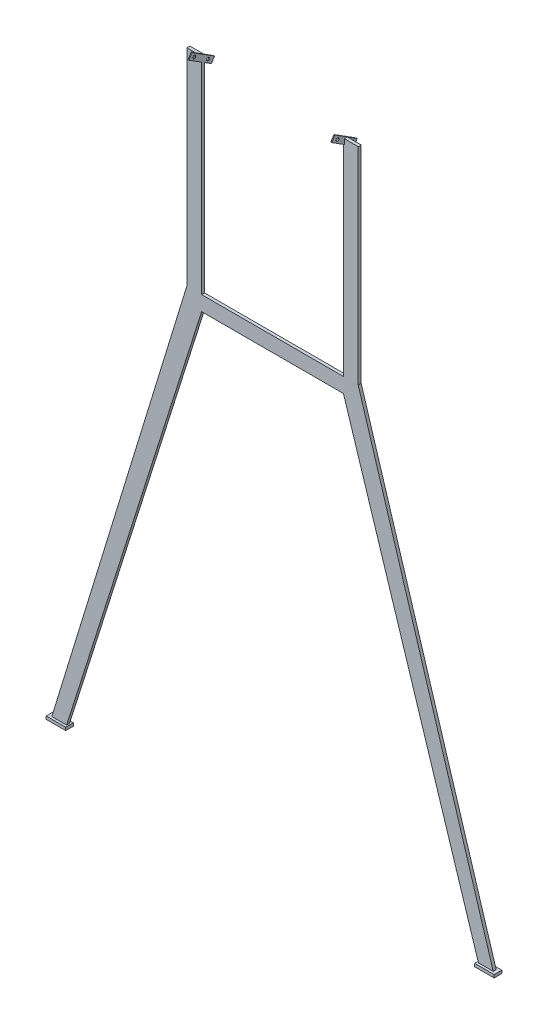
SolidWorks part; units mm, degrees
ref_plane "Front Plane" through (0, 0, 0) normal (0, 0, 1) x (1, 0, 0)
ref_plane "Top Plane" through (0, 0, 0) normal (0, 1, 0) x (1, 0, 0)
ref_plane "Right Plane" through (0, 0, 0) normal (1, 0, 0) x (0, 0, -1)
sketch "Sketch2" plane through (0, 0, 0) normal (0, 0, 1) x (1, 0, 0)
  line L1 (-670.4947, 662.5442) -> (829.5053, 662.5442)
  line L2 (-670.4947, 662.5442) -> (-670.4947, -1536.0258)
  line L3 (-670.4947, -1536.0258) -> (829.5053, -1536.0258)
  line L4 (829.5053, 662.5442) -> (829.5053, -1536.0258)
  line L5 (-160.4947, 662.5442) -> (319.5053, 662.5442)
  dimension "D1" = 1500
  dimension "D2" = 2198.57
extrude "Boss-Extrude1" add sketch "Sketch2" along normal blind 10 contours L4 L1 L2 L3
sketch "Sketch3" plane through (0, 0, 10) normal (0, 0, 1) x (1, 0, 0)
  line L0 (-670.4947, 662.5442) -> (829.5053, 662.5442) construction
  line L1 (-160.4947, 662.5442) -> (319.5053, 662.5442)
  line L2 (-160.4947, 662.5442) -> (-160.4947, -36.0262)
  line L3 (-160.4947, -36.0262) -> (319.5053, -36.0262)
  line L4 (319.5053, 662.5442) -> (319.5053, -36.0262)
  line L5 (-210.4947, 662.5442) -> (-210.4947, -36.0262)
  line L6 (-210.4947, -36.0262) -> (-670.4947, -36.0262)
  line L7 (-670.4947, 662.5442) -> (-670.4947, -1536.0258) construction
  line L8 (-670.4947, -36.0262) -> (-670.4947, 662.5442)
  line L9 (-670.4947, 662.5442) -> (-210.4947, 662.5442)
  line L10 (369.5053, 662.5442) -> (369.5053, -36.0262)
  line L11 (369.5053, -36.0262) -> (829.5053, -36.0262)
  line L12 (829.5053, 662.5442) -> (829.5053, -1536.0258) construction
  line L13 (829.5053, -36.0262) -> (829.5053, 662.5442)
  line L14 (829.5053, 662.5442) -> (369.5053, 662.5442)
  dimension "D1" = 510
  dimension "D2" = 480
  dimension "D3" = 698.5704
  dimension "D4" = 460
  dimension "D5" = 460
extrude "Cut-Extrude1" cut sketch "Sketch3" against normal through all
sketch "Sketch9" plane through (0, 0, 0) normal (0, 0, -1) x (-1, 0, 0)
  line L0 (-369.5053, -36.0262) -> (-829.5053, -36.0262)
  line L5 (-369.5053, -36.0262) -> (-829.5053, -1536.0258)
  line L6 (-829.5053, -36.0262) -> (-829.5053, -1536.0258)
  line L7 (210.4947, -36.0262) -> (670.4947, -1536.0258)
  line L8 (670.4947, -1536.0258) -> (670.4947, -36.0262)
  line L9 (670.4947, -36.0262) -> (210.4947, -36.0262)
extrude "Cut-Extrude3" cut sketch "Sketch9" against normal blind 10
sketch "Sketch10" plane through (0, 0, 0) normal (0, 0, -1) x (-1, 0, 0)
  line L0 (-319.5053, -86.0262) -> (-779.5053, -1536.0258)
  line L2 (670.4947, -1536.0258) -> (-829.5053, -1536.0258) construction
  line L3 (-779.5053, -1536.0258) -> (620.4947, -1536.0258)
  line L4 (620.4947, -1536.0258) -> (160.4947, -86.0262)
  line L5 (160.4947, -86.0262) -> (-319.5053, -86.0262)
  dimension "D1" = 480
  dimension "D2" = 50
  dimension "D3" = 0
  dimension "D4" = 50
  dimension "D5" = 1400
extrude "Cut-Extrude4" cut sketch "Sketch10" against normal through all contours L5 L0 L3 L4
sketch "Sketch11" plane through (319.5053, 0, 0) normal (-1, 0, 0) x (0, 0, 1)
  line L0 (0, 662.5442) -> (42.2463, 689.2883)
  line L1 (0, 662.5442) -> (-33.797, 641.1488)
  line L2 (-33.797, 641.1488) -> (-23.0994, 624.2503)
  line L3 (-23.0994, 624.2503) -> (52.944, 672.3898)
  line L4 (52.944, 672.3898) -> (42.2463, 689.2883)
  dimension "D1" = 50
  dimension "D2" = 40
  dimension "D3" = 20
extrude "Boss-Extrude2" add sketch "Sketch11" against normal blind 3
sketch "Sketch12" plane through (-160.4947, 0, 0) normal (1, 0, 0) x (0, 0, -1)
  line L5 (0, 662.5442) -> (33.797, 641.1488)
  line L6 (0, 662.5442) -> (-42.2463, 689.2883)
  line L7 (-42.2463, 689.2883) -> (-52.944, 672.3898)
  line L8 (-52.944, 672.3898) -> (23.0994, 624.2503)
  line L9 (23.0994, 624.2503) -> (33.797, 641.1488)
  dimension "D1" = 50
  dimension "D2" = 90
  dimension "D3" = 20
extrude "Boss-Extrude3" add sketch "Sketch12" against normal blind 3
sketch "Sketch13" plane through (-160.4947, 0, 0) normal (1, 0, 0) x (0, 0, -1)
  line L0 (33.797, 641.1488) -> (-42.2463, 689.2883) construction
  circle A0 centre (-34.6839, 672.6656) radius 5
  circle A1 centre (12.0373, 643.0886) radius 5
  dimension "D1" = 10
  dimension "D2" = 10
  dimension "D3" = 10
  dimension "D4" = 10
extrude "Cut-Extrude5" cut sketch "Sketch13" against normal through all
sketch "Sketch14" plane through (319.5053, 0, 0) normal (-1, 0, 0) x (0, 0, 1)
  line L0 (42.2463, 689.2883) -> (-33.797, 641.1488) construction
  circle A0 centre (32.8959, 671.5337) radius 5
  circle A1 centre (-16.2565, 640.4126) radius 5
  dimension "D1" = 10
  dimension "D2" = 10
  dimension "D3" = 10.0042
  dimension "D4" = 10
extrude "Cut-Extrude6" cut sketch "Sketch14" against normal through all
sketch "Sketch15" plane through (0, -1536.0258, 0) normal (0, -1, 0) x (1, 0, 0)
  line L0 (837.5053, 18) -> (837.5053, -8)
  line L1 (829.5053, 10) -> (779.5053, 10)
  line L2 (829.5053, 10) -> (829.5053, 0)
  line L3 (829.5053, 0) -> (779.5053, 0)
  line L4 (779.5053, 10) -> (779.5053, 0)
  line L5 (837.5053, -8) -> (771.5053, -8)
  line L6 (771.5053, 18) -> (771.5053, -8)
  line L7 (837.5053, 18) -> (771.5053, 18)
  dimension "D1" = 8
extrude "Boss-Extrude5" add sketch "Sketch15" against normal blind 10 contours L0 L5 L6 L7
sketch "Sketch16" plane through (0, -1536.0258, 0) normal (0, -1, 0) x (1, 0, 0)
  line L0 (-678.4947, -8) -> (-678.4947, 18)
  line L1 (-670.4947, 0) -> (-620.4947, 0)
  line L2 (-670.4947, 0) -> (-670.4947, 10)
  line L3 (-670.4947, 10) -> (-620.4947, 10)
  line L4 (-620.4947, 0) -> (-620.4947, 10)
  line L5 (-678.4947, 18) -> (-612.4947, 18)
  line L6 (-612.4947, -8) -> (-612.4947, 18)
  line L7 (-678.4947, -8) -> (-612.4947, -8)
  dimension "D1" = 8
extrude "Boss-Extrude9" add sketch "Sketch16" against normal blind 10 contours L0 L5 L6 L7
